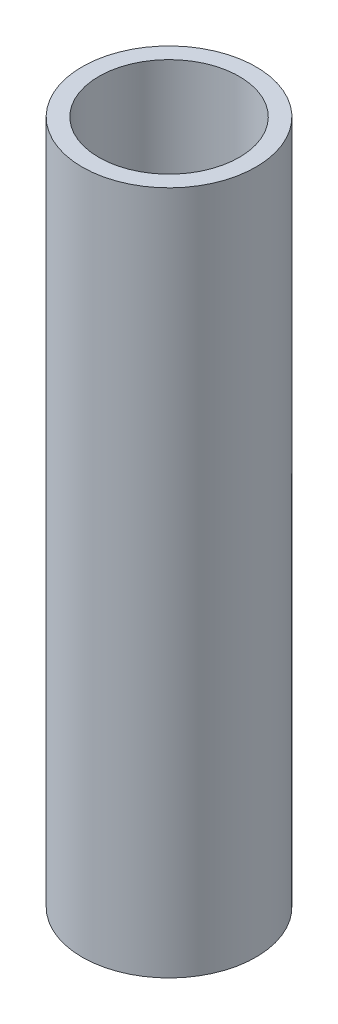
SolidWorks part; units mm, degrees
material "6061-T6 (SS)"
ref_plane "Front Plane" through (0, 0, 0) normal (0, 0, 1) x (1, 0, 0)
ref_plane "Top Plane" through (0, 0, 0) normal (0, 1, 0) x (1, 0, 0)
ref_plane "Right Plane" through (0, 0, 0) normal (1, 0, 0) x (0, 0, -1)
sketch "Sketch1" plane through (0, 0, 0) normal (0, 1, 0) x (1, 0, 0)
  circle A0 centre (0, 0) radius 2.667
  circle A1 centre (0, 0) radius 3.302
  dimension "D1" = 6.604
  dimension "D2" = 5.334
extrude "Boss-Extrude1" add sketch "Sketch1" along normal blind 26
move or copy body "Body-Move/Copy1" bodies to move or copy 101
